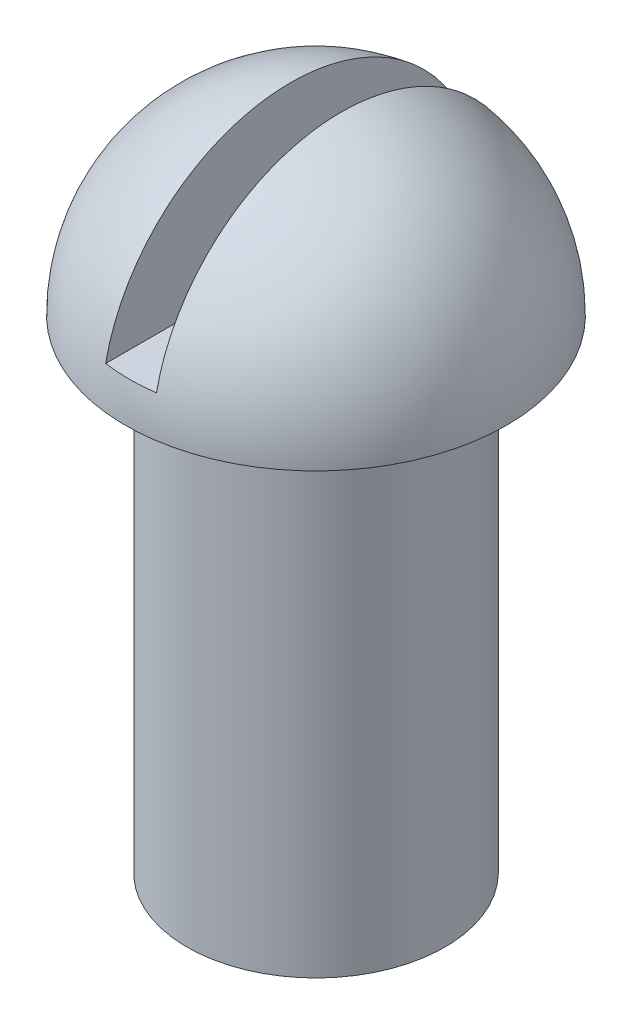
SolidWorks part; units mm, degrees
ref_plane "Front Plane" through (0, 0, 0) normal (0, 0, 1) x (1, 0, 0)
ref_plane "Top Plane" through (0, 0, 0) normal (0, 1, 0) x (1, 0, 0)
ref_plane "Right Plane" through (0, 0, 0) normal (1, 0, 0) x (0, 0, -1)
sketch "Sketch1" plane through (0, 0, 0) normal (0, 0, 1) x (1, 0, 0)
  line L0 (0, 53) -> (0, 0)
  line L1 (0, 0) -> (10.15, 0)
  line L2 (10.15, 0) -> (10.15, 38)
  line L3 (10.15, 38) -> (15, 38)
  arc A0 (0, 53) -> (15, 38) centre (0, 38) cw
  point P7 (0, 0)
  point P8 (15.0436, 38)
  point P9 (17.0988, 38)
  dimension "D1" = 15
  dimension "D2" = 38
  dimension "D3" = 10.15
  dimension "D4" = 15
revolve "Revolve1" add sketch "Sketch1" angle 360 about L0
sketch "Sketch2" plane through (0, 0, 0) normal (0, 0, 1) x (1, 0, 0)
  line L1 (-2, 60.7213) -> (2, 60.7213)
  line L2 (-2, 60.7213) -> (-2, 41)
  line L3 (-2, 41) -> (2, 41)
  line L4 (2, 60.7213) -> (2, 41)
  line L5 (0, 0) -> (0, 21.3289) construction
  line L6 (-15, 38) -> (15, 38) construction
  dimension "D1" = 4
  dimension "D2" = 3
extrude "Cut-Extrude1" cut sketch "Sketch2" against normal through all both and the other way through all
